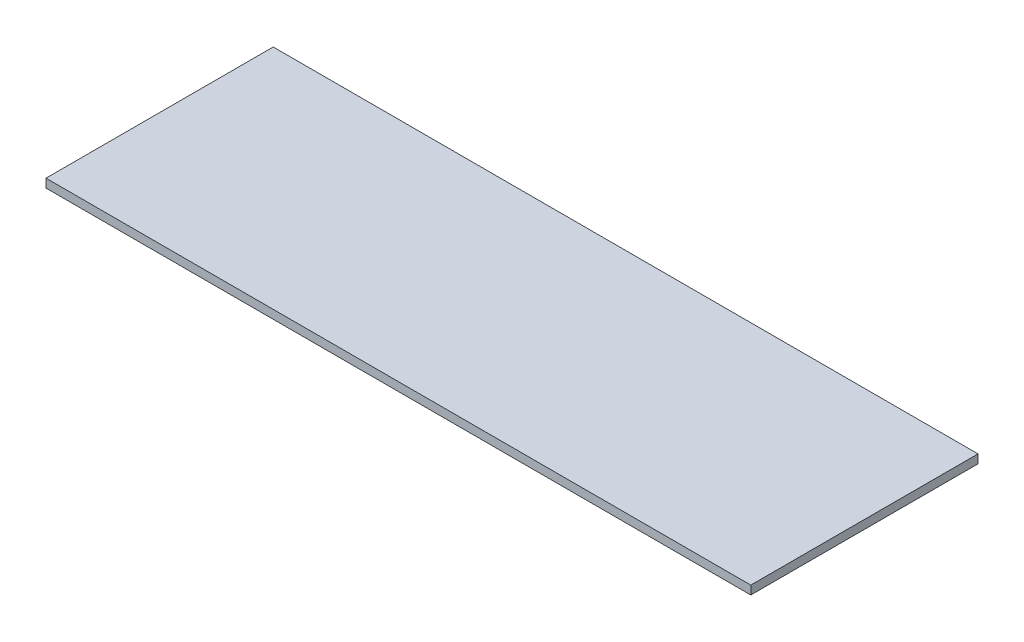
SolidWorks part; units mm, degrees
ref_plane "Front Plane" through (0, 0, 0) normal (0, 0, 1) x (1, 0, 0)
ref_plane "Top Plane" through (0, 0, 0) normal (0, 1, 0) x (1, 0, 0)
ref_plane "Right Plane" through (0, 0, 0) normal (1, 0, 0) x (0, 0, -1)
sketch "Sketch1" plane through (0, 0, 0) normal (0, 1, 0) x (1, 0, 0)
  line L1 (-167.5, 54) -> (167.5, 54)
  line L2 (-167.5, 54) -> (-167.5, -54)
  line L3 (-167.5, -54) -> (167.5, -54)
  line L4 (167.5, 54) -> (167.5, -54)
  line L5 (-167.5, 54) -> (167.5, -54) construction
  line L6 (-167.5, -54) -> (167.5, 54) construction
  point P0 (0, 0)
  dimension "D1" = 335
  dimension "D2" = 108
extrude "Boss-Extrude2" add sketch "Sketch1" along normal blind 4.0952
